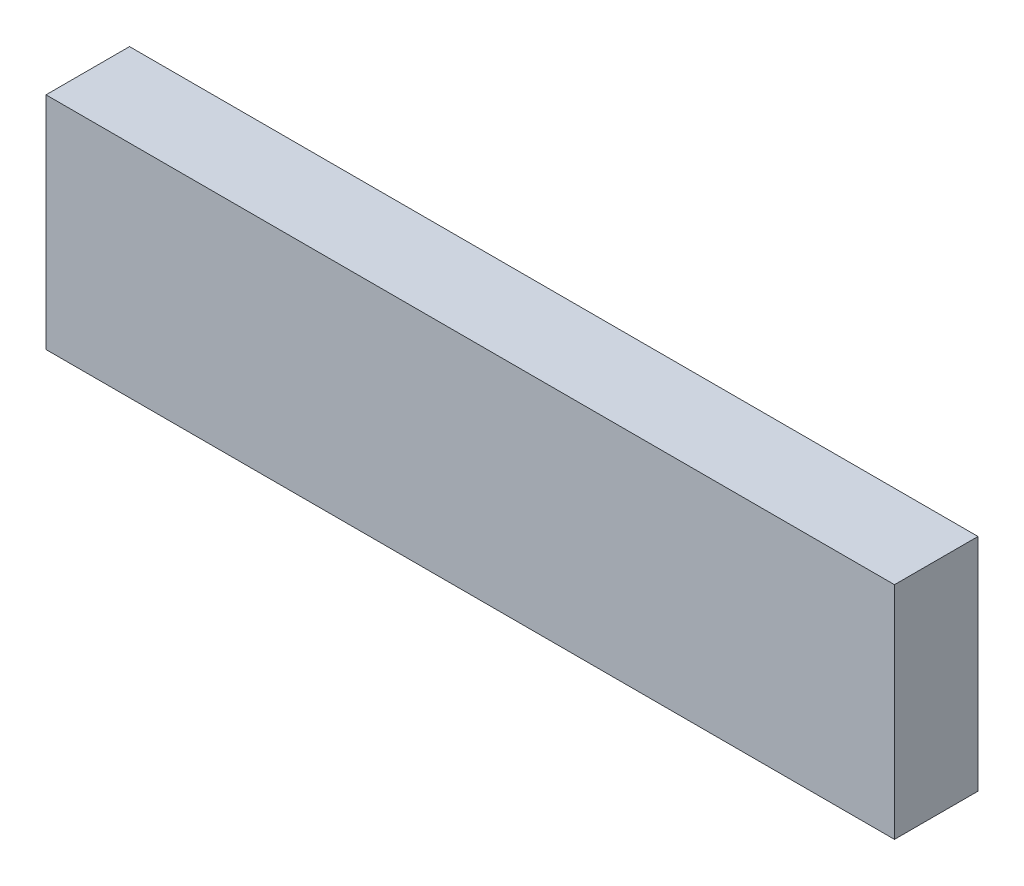
SolidWorks part; units mm, degrees
ref_plane "Plan de face" through (0, 0, 0) normal (0, 0, 1) x (1, 0, 0)
ref_plane "Plan de dessus" through (0, 0, 0) normal (0, 1, 0) x (1, 0, 0)
ref_plane "Plan de droite" through (0, 0, 0) normal (1, 0, 0) x (0, 0, -1)
sketch "Esquisse1" plane through (0, 0, 0) normal (0, 0, 1) x (1, 0, 0)
  line L0 (-1.27, 1.3716) -> (8.89, 1.3716)
  line L1 (8.89, 1.3716) -> (8.89, -1.27)
  line L2 (8.89, -1.27) -> (-1.27, -1.27)
  line L3 (-1.27, -1.27) -> (-1.27, 1.3716)
extrude "Component_Outline" add sketch "Esquisse1" along normal blind 1 separate body
sketch3d "Esquisse3D1"
  line L0 (0, 0, 0) -> (1, 0, 0)
  line L1 (0, 0, 0) -> (0, 1, 0)
  line L2 (0, 0, 0) -> (0, 0, 1)
  point P0 (0, 0, 0)
